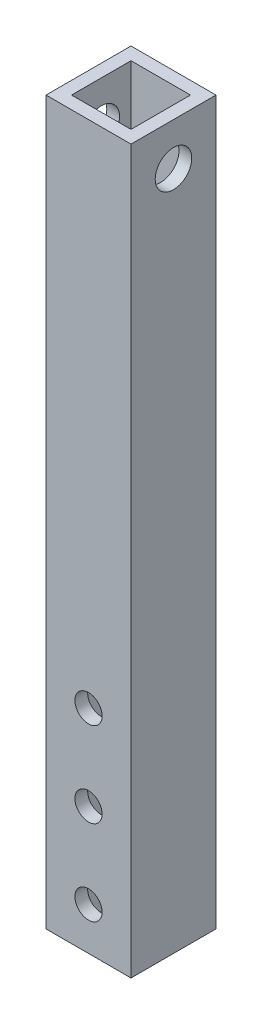
SolidWorks part; units mm, degrees
material "5052-H34"
ref_plane "正面" through (0, 0, 0) normal (0, 0, 1) x (1, 0, 0)
ref_plane "平面" through (0, 0, 0) normal (0, 1, 0) x (1, 0, 0)
ref_plane "右側面" through (0, 0, 0) normal (1, 0, 0) x (0, 0, -1)
sketch "ｽｹｯﾁ1" plane through (0, 0, 0) normal (0, 1, 0) x (1, 0, 0)
  line L1 (-5, 5) -> (5, 5)
  line L2 (-5, 5) -> (-5, -5)
  line L3 (-5, -5) -> (5, -5)
  line L4 (5, 5) -> (5, -5)
  line L5 (-5, 5) -> (5, -5) construction
  line L6 (-5, -5) -> (5, 5) construction
  point P0 (0, 0)
  dimension "D1" = 10
  dimension "D2" = 10
extrude "押し出し-薄板1" add sketch "ｽｹｯﾁ1" along normal blind 85 thin
sketch "ｽｹｯﾁ2" plane through (0, 0, 5) normal (0, 0, 1) x (1, 0, 0)
  line L0 (0, 0) -> (0, 25) construction
  line L1 (-5, 85) -> (5, 85) construction
  circle A0 centre (0, 25) radius 1.6
  circle A1 centre (0, 5) radius 1.6
  circle A2 centre (0, 15) radius 1.6
  point P6 (0, 15)
  dimension "D1" = 3.2
  dimension "D2" = 10
  dimension "D3" = 20
  dimension "D4" = 70
extrude "ｶｯﾄ - 押し出し1" cut sketch "ｽｹｯﾁ2" against normal through all
sketch "ｽｹｯﾁ3" plane through (5, 0, 0) normal (1, 0, 0) x (0, 0, -1)
  line L0 (0, 85) -> (0, 80) construction
  line L1 (-5, 85) -> (5, 85) construction
  circle A0 centre (0, 80) radius 2.15
  dimension "D2" = 4.3
  dimension "D1" = 5
extrude "ｶｯﾄ - 押し出し2" cut sketch "ｽｹｯﾁ3" against normal through all
